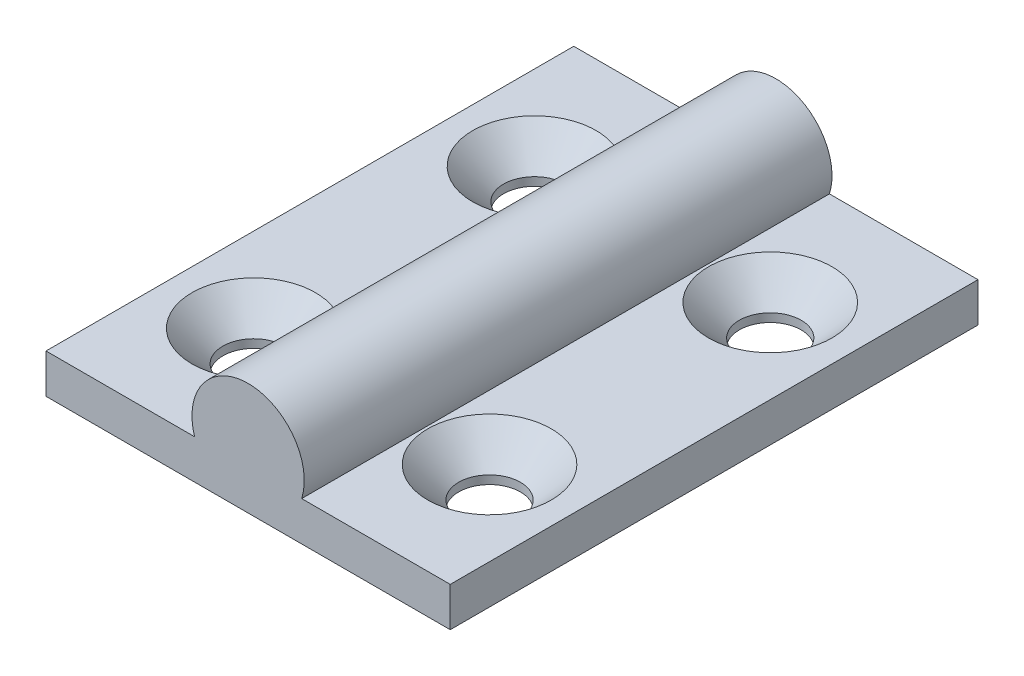
SolidWorks part; units mm, degrees
ref_plane "Front Plane" through (0, 0, 0) normal (0, 0, 1) x (1, 0, 0)
ref_plane "Top Plane" through (0, 0, 0) normal (0, 1, 0) x (1, 0, 0)
ref_plane "Right Plane" through (0, 0, 0) normal (1, 0, 0) x (0, 0, -1)
sketch "Sketch1" plane through (0, 0, 0) normal (0, 0, 1) x (1, 0, 0)
  line L0 (0, -5) -> (-18, -5)
  line L1 (-18, -5) -> (-18, -1.5)
  line L2 (-18, -1.5) -> (-4.7697, -1.5)
  circle A0 centre (0, 0) radius 5
  dimension "D1" = 10
  dimension "D2" = 18
  dimension "D3" = 3.5
extrude "Boss-Extrude1" add sketch "Sketch1" along normal mid plane 47 contours A0 L2 L1 L0 | A0
sketch "Sketch2" plane through (0, -1.5, 0) normal (0, 1, 0) x (1, 0, 0)
  line L0 (0, 0) -> (-10.5, 0) construction
  line L1 (-10.5, -12.5) -> (-10.5, 12.5) construction
  line L2 (0, 0) -> (0, 50000) construction
  point P7 (-10.5, 0)
  dimension "D1" = 10.5
  dimension "D2" = 25
hole_wizard "Hole1" positions "Sketch3" profile "Sketch5" legacy end condition through all
sketch "Sketch3" plane through (0, -1.5, 0) normal (0, 1, 0) x (1, 0, 0)
  point P0 (-10.5, 12.5)
  point P3 (-10.5, -12.5)
sketch "Sketch5" plane through (-10.5, -1.5, -12.5) normal (1, 0, 0) x (0, 0, 1)
  line L0 (0, 0) -> (0, 5.1524)
  line L1 (0, 5.1524) -> (2.75, 3.5)
  line L2 (2.75, 3.5) -> (2.75, 2.75)
  line L3 (2.75, 2.75) -> (5.5, 0)
  line L4 (5.5, 0) -> (0, 0)
  line L5 (0, -14.3089) -> (0, 102.4216) construction
  line L6 (0, 5.1524) -> (-2.75, 3.5) construction
  line L7 (-2.75, 2.75) -> (-5.5, 0) construction
  dimension "Diameter" = 5.5
  dimension "Depth" = 3.5
  dimension "C-Sink Diameter" = 11
  dimension "C-Sink Angle" = 90
  dimension "Drill Angle" = 118
ref_point "Point1"
ref_plane "Plane1" through (-10.5, 0, 0) normal (-1, 0, 0) x (0, 0, 1)
mirror "Mirror1" about plane through (0, 0, 0) normal (1, 0, 0) of "Boss-Extrude1"
mirror "Mirror2" about plane through (0, 0, 0) normal (1, 0, 0) of "Hole1"
